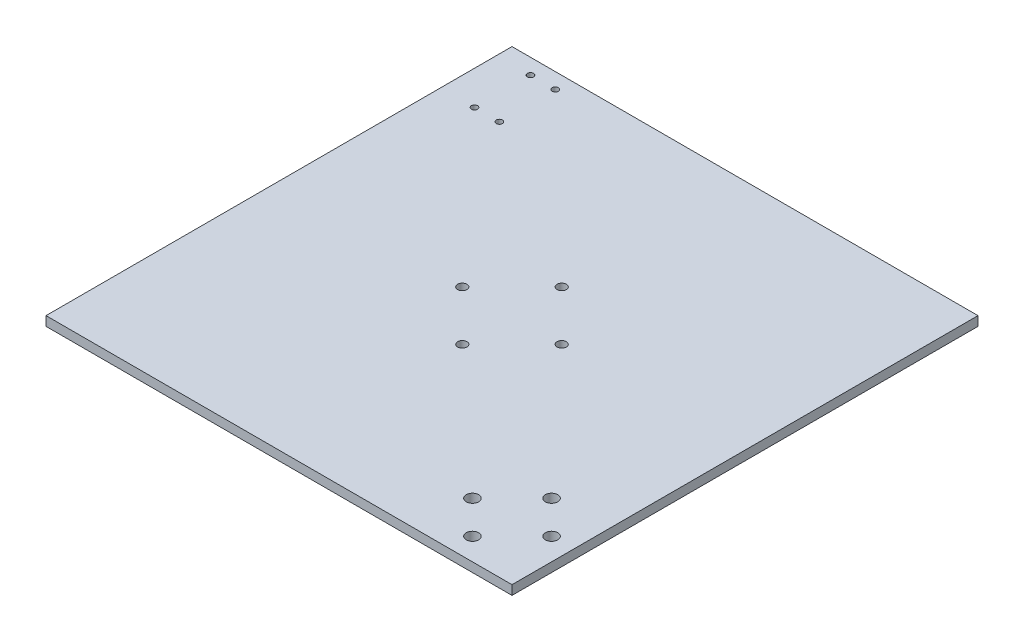
SolidWorks part; units mm, degrees
ref_plane "Front Plane" through (0, 0, 0) normal (0, 0, 1) x (1, 0, 0)
ref_plane "Top Plane" through (0, 0, 0) normal (0, 1, 0) x (1, 0, 0)
ref_plane "Right Plane" through (0, 0, 0) normal (1, 0, 0) x (0, 0, -1)
sketch "Sketch1" plane through (0, 0, 0) normal (0, 1, 0) x (1, 0, 0)
  line L1 (0, 0) -> (150, 0)
  line L2 (0, 0) -> (0, 150)
  line L3 (0, 150) -> (150, 150)
  line L4 (150, 0) -> (150, 150)
  dimension "D1" = 150
  dimension "D2" = 150
extrude "Boss-Extrude1" add sketch "Sketch1" along normal blind 3
sketch "Sketch2" plane through (0, 3, 0) normal (0, 1, 0) x (1, 0, 0)
  line L0 (150, 150) -> (0, 150) construction
  line L1 (0, 150) -> (0, 0) construction
  line L2 (75, 75) -> (75, 150) construction
  line L3 (75, 75) -> (210.7511, 75) construction
  line L4 (59, 75) -> (75, 75) construction
  line L5 (75, 75) -> (75, 91) construction
  line L6 (91, 75) -> (75, 75) construction
  line L7 (75, 59) -> (75, 75) construction
  circle A0 centre (75, 75) radius 3.5 construction
  circle A1 centre (75, 59) radius 1.5
  circle A2 centre (59, 75) radius 1.5
  circle A3 centre (75, 91) radius 1.5
  circle A4 centre (91, 75) radius 1.5
  circle A5 centre (18.93, 145) radius 1
  circle A6 centre (10.93, 145) radius 1
  circle A7 centre (18.93, 127) radius 1
  circle A8 centre (10.93, 127) radius 1
  dimension "D1" = 7
  dimension "D2" = 3
  dimension "D4" = 18
  dimension "D5" = 2
  dimension "D3" = 16
  dimension "D6" = 8
  dimension "D7" = 5
  dimension "D8" = 10.93
  dimension "D9" = 75
  dimension "D10" = 75
extrude "Cut-Extrude1" cut sketch "Sketch2" against normal blind 10
sketch "Sketch5" plane through (0, 3, 0) normal (0, 1, 0) x (1, 0, 0)
  line L0 (132.2757, 30.4523) -> (119.5478, 17.7244) construction
  line L1 (119.5478, 17.7244) -> (130.1544, 7.1177) construction
  line L2 (130.1544, 7.1177) -> (142.8823, 19.8457) construction
  line L3 (142.8823, 19.8457) -> (132.2757, 30.4523) construction
  line L4 (0, 0) -> (150, 0) construction
  line L5 (0, 150) -> (0, 0) construction
  line L6 (0, 0) -> (150, 150) construction
  circle A0 centre (132.2757, 30.4523) radius 2
  circle A1 centre (119.5478, 17.7244) radius 2
  circle A2 centre (130.1544, 7.1177) radius 2
  circle A3 centre (142.8823, 19.8457) radius 2
  dimension "D5" = 4
  dimension "D1" = 7.1177
  dimension "D2" = 18
  dimension "D3" = 15
  dimension "D4" = 130.1544
  dimension "D6" = 45
extrude "Cut-Extrude2" cut sketch "Sketch5" against normal blind 10
